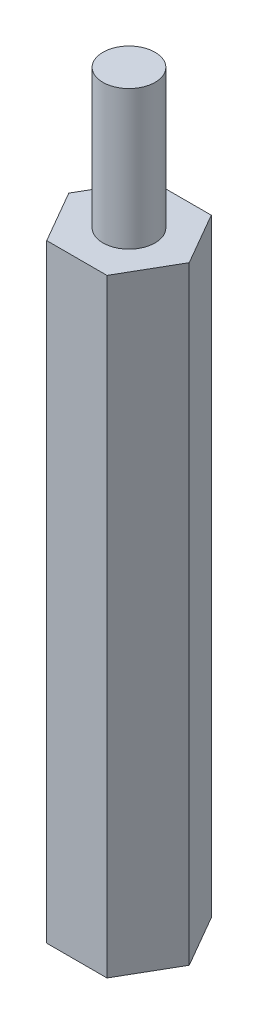
SolidWorks part; units mm, degrees
ref_plane "Front Plane" through (0, 0, 0) normal (0, 0, 1) x (1, 0, 0)
ref_plane "Top Plane" through (0, 0, 0) normal (0, 1, 0) x (1, 0, 0)
ref_plane "Right Plane" through (0, 0, 0) normal (1, 0, 0) x (0, 0, -1)
sketch "Sketch1" plane through (0, 0, 0) normal (0, 1, 0) x (1, 0, 0)
  line L1 (1.7321, -3) -> (3.4641, 0)
  line L2 (3.4641, 0) -> (1.7321, 3)
  line L3 (1.7321, 3) -> (-1.7321, 3)
  line L4 (-1.7321, 3) -> (-3.4641, 0)
  line L5 (-3.4641, 0) -> (-1.7321, -3)
  line L6 (-1.7321, -3) -> (1.7321, -3)
  circle A0 centre (0, 0) radius 3 construction
  dimension "D1" = 6
extrude "Boss-Extrude1" add sketch "Sketch1" along normal blind 35
sketch "Sketch2" plane through (0, 35, 0) normal (0, 1, 0) x (1, 0, 0)
  circle A0 centre (0, 0) radius 1.5
  dimension "D1" = 3
extrude "Boss-Extrude2" add sketch "Sketch2" along normal blind 8
